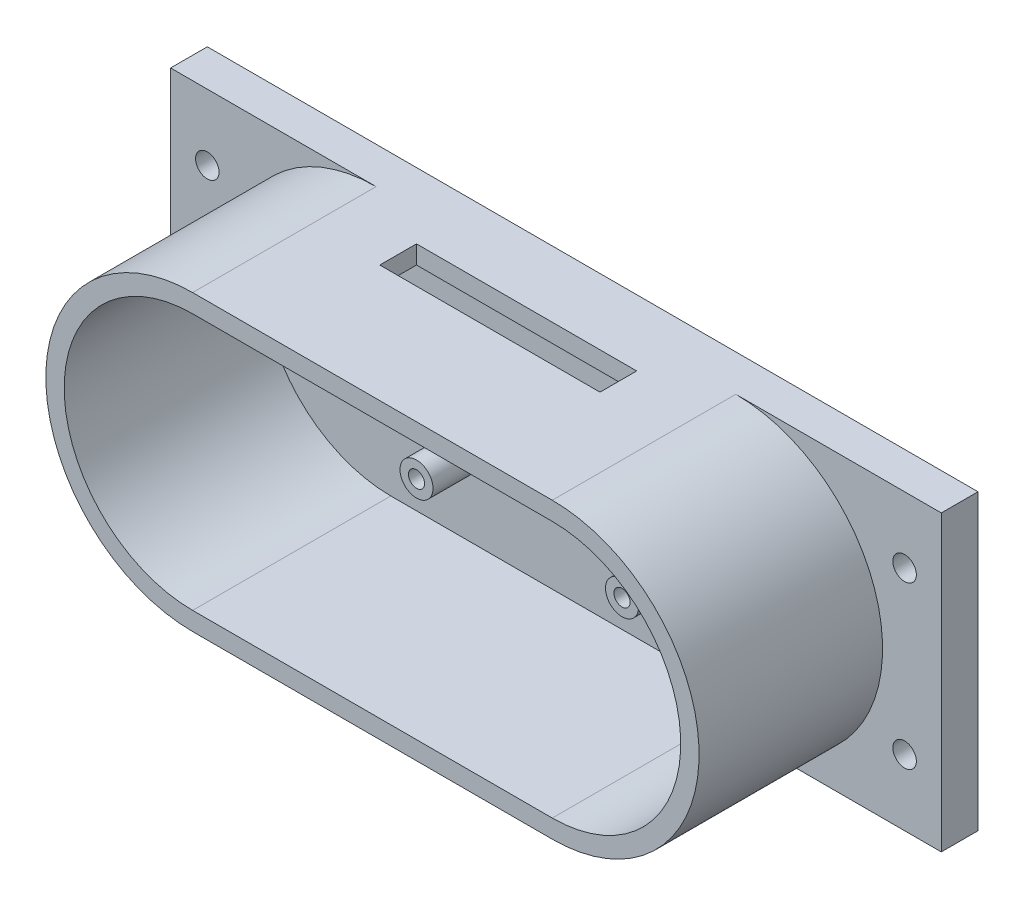
SolidWorks part; units mm, degrees
material "ABS"
ref_plane "Спереди" through (0, 0, 0) normal (0, 0, 1) x (1, 0, 0)
ref_plane "Сверху" through (0, 0, 0) normal (0, 1, 0) x (1, 0, 0)
ref_plane "Справа" through (0, 0, 0) normal (1, 0, 0) x (0, 0, -1)
sketch "Эскиз1" plane through (0, 0, 0) normal (0, 0, 1) x (1, 0, 0)
  line L0 (0, 0) -> (0, -20) construction
  line L1 (-24.5, 20) -> (24.5, 20)
  line L3 (-24.5, -20) -> (24.5, -20)
  line L5 (-31, 0) -> (31, 0) construction
  line L6 (-31, 10) -> (31, 10) construction
  line L7 (-31, -10) -> (31, -10) construction
  arc A1 (24.5, 20) -> (24.5, -20) centre (24.5, 0) cw
  arc A3 (-24.5, 20) -> (-24.5, -20) centre (-24.5, 0) ccw
  arc A5 (-31, 10) -> (-31, -10) centre (-31, 0) ccw construction
  arc A6 (31, -10) -> (31, 10) centre (31, 0) ccw construction
  point P13 (0, 0)
  dimension "D3" = 20
  dimension "D4" = 10
  dimension "D5" = 82
  dimension "D2" = 89
  dimension "D1" = 40
extrude "Бобышка-Вытянуть1" add sketch "Эскиз1" along normal blind 30
shell "Оболочка1" thickness 2.5
sketch "Эскиз2" plane through (0, 0, 0) normal (0, 0, 1) x (1, 0, 0)
  line L0 (-24.5, 20) -> (-52.5, 20)
  line L1 (-52.5, 20) -> (-52.5, -20)
  line L2 (24.5, 20) -> (-24.5, 20)
  line L3 (-24.5, -20) -> (24.5, -20)
  line L6 (-52.5, -20) -> (-24.5, -20)
  line L7 (24.5, -20) -> (52.5, -20)
  line L8 (52.5, -20) -> (52.5, 20)
  line L9 (52.5, 20) -> (24.5, 20)
  arc A2 (24.5, -20) -> (24.5, 20) centre (24.5, 0) ccw
  arc A3 (-24.5, 20) -> (-24.5, -20) centre (-24.5, 0) ccw
  arc A4 (24.5, -20) -> (24.5, 20) centre (24.5, 0) ccw
  arc A5 (-24.5, 20) -> (-24.5, -20) centre (-24.5, 0) ccw
  dimension "D2" = 105
  dimension "D1" = 0
extrude "Бобышка-Вытянуть2" add sketch "Эскиз2" along normal blind 5
hole_wizard "Отверстие с зазором M31" positions "Эскиз4" profile "Эскиз3" hole size "M3" standard "ISO" end condition through all
sketch "Эскиз4" plane through (0, 0, 30) normal (0, 0, 1) x (1, 0, 0)
  line L0 (-31, 0) -> (31, 0) construction
  line L1 (-30, 0) -> (30, 0) construction
  line L2 (0, 0) -> (0, -20) construction
  line L3 (0, 0) -> (0, -17.5) construction
  point P0 (-47.5, 11)
  point P6 (-47.5, -11)
  point P11 (47.5, -11)
  point P12 (47.5, 11)
  dimension "D1" = 22
  dimension "D2" = 95
sketch "Эскиз3" plane through (-47.5, 11, 30) normal (1, 0, 0) x (0, -1, 0)
  line L0 (0, 0) -> (0, 30)
  line L1 (0, 30) -> (1.6, 30)
  line L2 (1.6, 30) -> (1.6, 0)
  line L5 (1.6, 0) -> (0, 0)
  line L11 (0, -6.35) -> (0, 107.95) construction
  dimension "Диаметр сквозного отверстия" = 3.2
  dimension "Глубина сквозного отверстия" = 30
sketch "Эскиз5" plane through (0, 0, 3) normal (0, 0, 1) x (1, 0, 0)
  circle A0 centre (-14, 6.75) radius 2.25
  circle A1 centre (14, 6.75) radius 2.25
  circle A2 centre (-14, -6.75) radius 2.25
  circle A3 centre (14, -6.75) radius 2.25
  dimension "D1" = 4.5
extrude "Бобышка-Вытянуть3" add sketch "Эскиз5" along normal blind 7
hole_wizard "Отверстие с зазором M21" positions "Эскиз7" profile "Эскиз6" hole size "M2" standard "DIN"
sketch "Эскиз7" plane through (0, 0, 10) normal (0, 0, 1) x (1, 0, 0)
  point P0 (-14, 6.75)
  point P3 (14, 6.75)
  point P6 (14, -6.75)
  point P9 (-14, -6.75)
sketch "Эскиз6" plane through (-14, 6.75, 10) normal (1, 0, 0) x (0, -1, 0)
  line L0 (0, 0) -> (0, 12.1609)
  line L1 (0, 12.1609) -> (1.1, 11.5)
  line L2 (1.1, 11.5) -> (1.1, 0)
  line L5 (1.1, 0) -> (0, 0)
  line L10 (0, 12.1609) -> (-1.1, 11.5) construction
  line L11 (0, -6.35) -> (0, 107.95) construction
  dimension "Диаметр отверстия" = 2.2
  dimension "Глубина отверстия" = 11.5
  dimension "Угол заточки сверла" = 118
sketch "Эскиз8" plane through (0, 20, 0) normal (0, 1, 0) x (1, 0, 0)
  line L0 (0, 0) -> (0, -9) construction
  line L1 (15, -14) -> (-15, -14)
  line L2 (15, -14) -> (15, -9)
  line L3 (15, -9) -> (-15, -9)
  line L4 (-15, -14) -> (-15, -9)
  line L5 (-31, 0) -> (31, 0) construction
  dimension "D1" = 9
  dimension "D2" = 5
  dimension "D3" = 30
extrude "Вырез-Вытянуть1" cut sketch "Эскиз8" against normal blind 5
